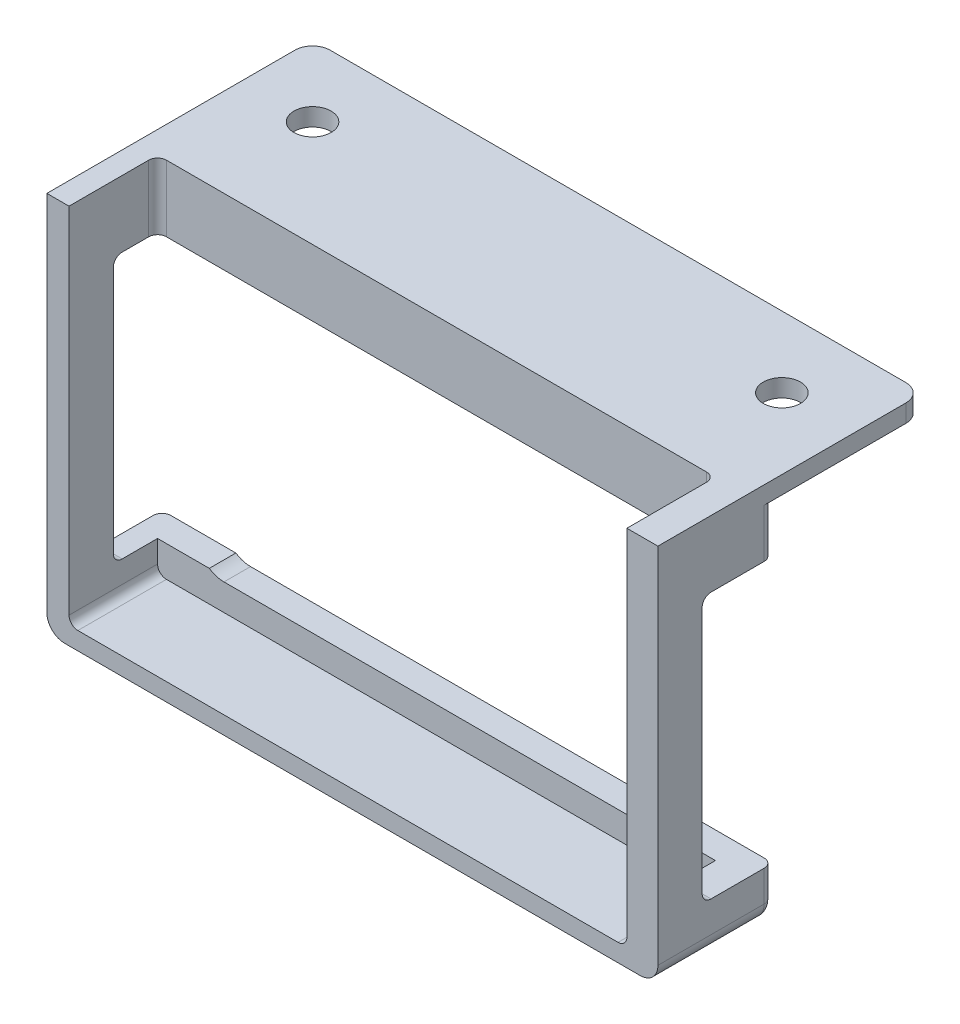
SolidWorks part; units mm, degrees
material "ABS"
ref_plane "前视基准面" through (0, 0, 0) normal (0, 0, 1) x (1, 0, 0)
ref_plane "上视基准面" through (0, 0, 0) normal (0, 1, 0) x (1, 0, 0)
ref_plane "右视基准面" through (0, 0, 0) normal (1, 0, 0) x (0, 0, -1)
sketch "草图1" plane through (0, 0, 0) normal (0, 1, 0) x (1, 0, 0)
  line L1 (34.5, -15) -> (-34.5, -15)
  line L2 (34.5, -15) -> (34.5, 15)
  line L3 (34.5, 15) -> (-34.5, 15)
  line L4 (-34.5, -15) -> (-34.5, 15)
  line L5 (34.5, -15) -> (-34.5, 15) construction
  line L6 (34.5, 15) -> (-34.5, -15) construction
  point P0 (0, 0)
  dimension "D1" = 69
  dimension "D2" = 30
extrude "凸台-拉伸1" add sketch "草图1" along normal blind 43
sketch "草图3" plane through (0, 43, 0) normal (0, 1, 0) x (1, 0, 0)
  line L0 (-34.5, -15) -> (34.5, -15) construction
  line L1 (-32, -15) -> (31, -15)
  line L2 (-32, -15) -> (-32, -5)
  line L3 (-32, -5) -> (31, -5)
  line L4 (31, -15) -> (31, -5)
  line L5 (-34.5, 15) -> (-34.5, -15) construction
  dimension "D1" = 63
  dimension "D2" = 10
  dimension "D3" = 2.5
extrude "切除-拉伸2" cut sketch "草图3" against normal blind 41
sketch "草图4" plane through (0, 0, 0) normal (0, -1, 0) x (-1, 0, 0)
  line L0 (-34.5, -15) -> (-34.5, 15) construction
  line L1 (34.5, 15) -> (-34.5, 15)
  line L2 (34.5, 15) -> (34.5, -2)
  line L3 (34.5, -2) -> (-34.5, -2)
  line L4 (-34.5, 15) -> (-34.5, -2)
  dimension "D1" = 17
extrude "切除-拉伸3" cut sketch "草图4" against normal blind 41
sketch "草图5" plane through (0, 41, 0) normal (0, -1, 0) x (-1, 0, 0)
  line L0 (34.5, -2) -> (34.5, 15) construction
  line L1 (34.5, 15) -> (-34.5, 15) construction
  circle A0 centre (26.5, 7) radius 2.1
  dimension "D1" = 4.2
  dimension "D2" = 8
  dimension "D3" = 8
extrude "切除-拉伸4" cut sketch "草图5" against normal through all
ref_plane "基准面1" through (0, 0, 0) normal (-1, 0, 0) x (0, 0, 1)
mirror "镜向1" about plane through (0, 0, 0) normal (-1, 0, 0) of "切除-拉伸4"
sketch "草图9" plane through (0, 0, 2) normal (0, 0, -1) x (-1, 0, 0)
  line L0 (-34.5, 0) -> (34.5, 0) construction
  line L1 (-27.5, 35) -> (27.5, 35)
  line L2 (-27.5, 35) -> (-27.5, 5)
  line L3 (-27.5, 5) -> (27.5, 5)
  line L4 (27.5, 35) -> (27.5, 5)
  line L5 (-27.5, 35) -> (27.5, 5) construction
  line L6 (-27.5, 5) -> (27.5, 35) construction
  point P0 (0, 20)
  dimension "D1" = 30
  dimension "D2" = 20
  dimension "D3" = 55
extrude "切除-拉伸5" cut sketch "草图9" against normal through all
fillet "圆角1" radius 3 4 edges at (27.5, 35, 3.5) (-27.5, 35, 3.5) (27.5, 5, 3.5) (-27.5, 5, 3.5)
fillet "圆角2" radius 2 4 edges at (-34.5, 42, -15) (34.5, 42, -15) (-34.5, 0, 8.5) (34.5, 0, 8.5)
fillet "圆角3" radius 1 2 edges at (31, 2, 10) (-32, 2, 10)
sketch "草图10" plane through (-34.5, 0, 0) normal (-1, 0, 0) x (0, 0, 1)
  line L0 (2, 41) -> (2, 2) construction
  line L1 (2, 5.5) -> (10, 5.5)
  line L2 (2, 5.5) -> (2, 35.5)
  line L3 (2, 35.5) -> (10, 35.5)
  line L4 (10, 5.5) -> (10, 35.5)
  line L6 (2, 2) -> (15, 2) construction
  dimension "D1" = 8
  dimension "D2" = 30
  dimension "D3" = 3.5
extrude "切除-拉伸6" cut sketch "草图10" against normal through all
fillet "圆角4" radius 1 6 edges at (-32, 39.25, 5) (31, 39.25, 5) (32.75, 5.5, 10) (32.75, 35.5, 10) (-33.25, 35.5, 10) (-33.25, 5.5, 10)
fillet "圆角5" radius 1 7 edges at (-33.9142, 0.5858, 2) (0, 0, 2) (33.9142, 0.5858, 2) (-34.5, 38.25, 2) (34.5, 38.25, 2) (-34.5, 3.75, 2) (34.5, 3.75, 2)
